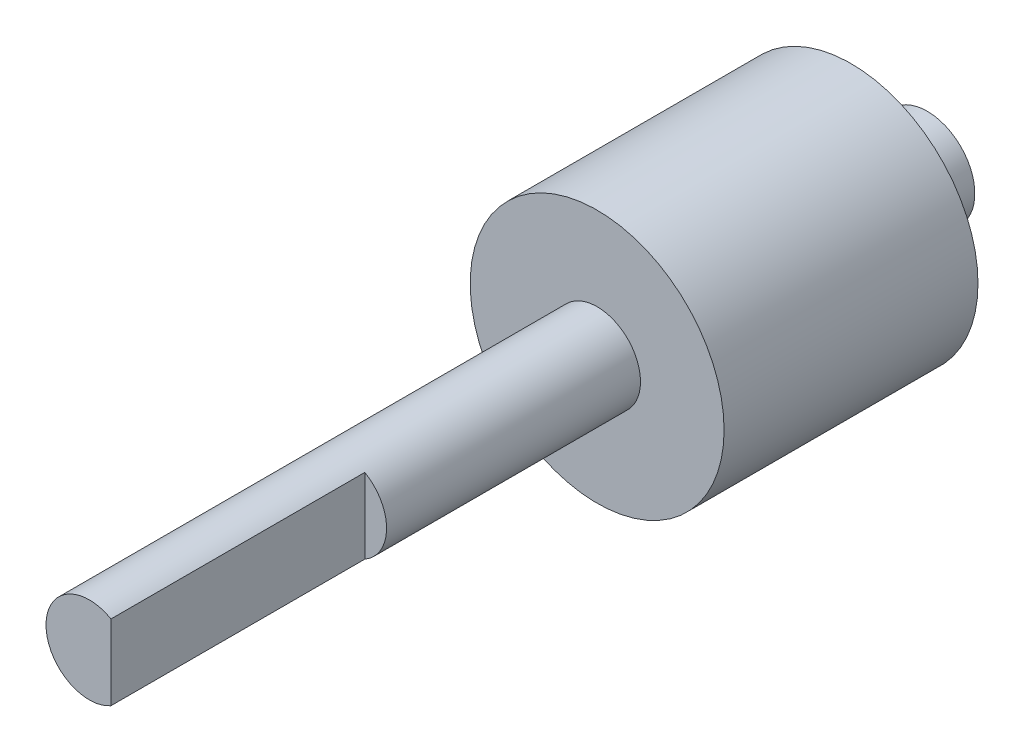
SolidWorks part; units mm, degrees
ref_plane "Front Plane" through (0, 0, 0) normal (0, 0, 1) x (1, 0, 0)
ref_plane "Top Plane" through (0, 0, 0) normal (0, 1, 0) x (1, 0, 0)
ref_plane "Right Plane" through (0, 0, 0) normal (1, 0, 0) x (0, 0, -1)
sketch "Sketch1" plane through (0, 0, 0) normal (0, 0, 1) x (1, 0, 0)
  circle A0 centre (-12.4444, 13.9222) radius 5
  dimension "D1" = 10
extrude "Boss-Extrude1" add sketch "Sketch1" along normal blind 10
sketch "Sketch2" plane through (0, 0, 10) normal (0, 0, 1) x (1, 0, 0)
  circle A0 centre (-12.4444, 13.9222) radius 1.707
  dimension "D1" = 3.414
extrude "Boss-Extrude3" add sketch "Sketch2" along normal blind 10
sketch "Sketch4" plane through (0, 0, 20) normal (0, 0, 1) x (1, 0, 0)
  line L0 (-11.5939, 15.4022) -> (-11.5939, 12.4422)
  arc A0 (-11.5939, 15.4022) -> (-11.5939, 12.4422) centre (-12.4444, 13.9222) ccw
  dimension "D1" = 3.414
  dimension "D2" = 2.96
extrude "Boss-Extrude4" add sketch "Sketch4" along normal blind 10
sketch "Sketch5" plane through (0, 0, 0) normal (0, 0, -1) x (-1, 0, 0)
  circle A0 centre (12.4444, 13.9222) radius 1.875
  dimension "D1" = 3.75
extrude "Boss-Extrude5" add sketch "Sketch5" along normal blind 3
